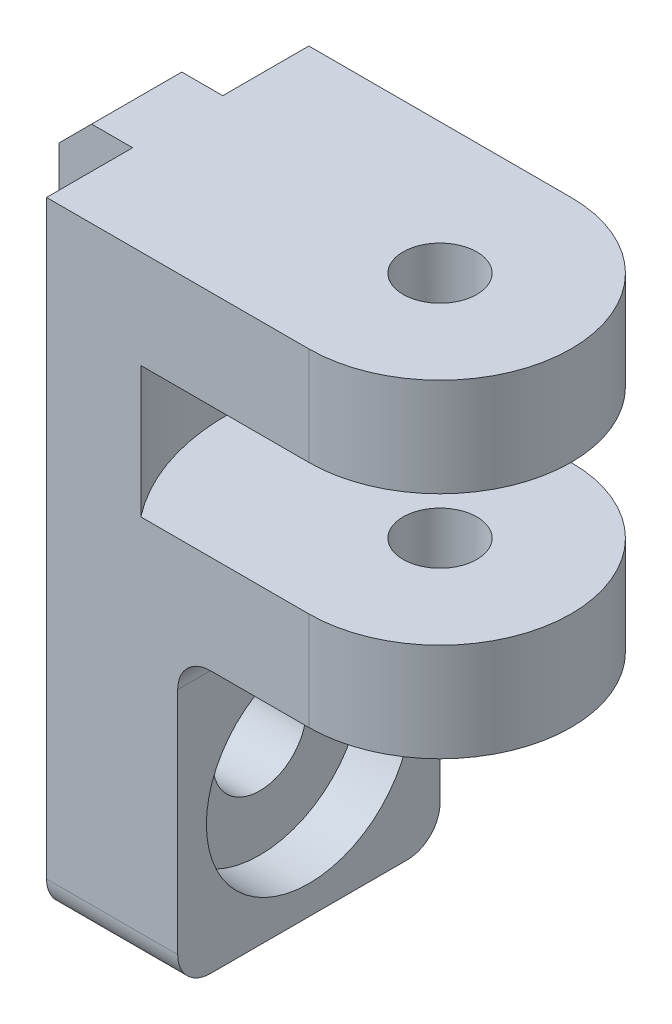
SolidWorks part; units mm, degrees
ref_plane "Front Plane" through (0, 0, 0) normal (0, 0, 1) x (1, 0, 0)
ref_plane "Top Plane" through (0, 0, 0) normal (0, 1, 0) x (1, 0, 0)
ref_plane "Right Plane" through (0, 0, 0) normal (1, 0, 0) x (0, 0, -1)
sketch "Sketch1" plane through (0, 0, 0) normal (1, 0, 0) x (0, 0, -1)
  line L0 (-32.8466, 35.9115) -> (-32.8466, -2.0885)
  line L1 (-48.8466, 35.9115) -> (-32.8466, 35.9115)
  line L5 (-32.8466, -2.0885) -> (-48.8466, -2.0885)
  line L6 (-48.8466, -2.0885) -> (-48.8466, 35.9115)
  dimension "D9" = 16
  dimension "D10" = 38
extrude "Boss-Extrude1" add sketch "Sketch1" along normal blind 8
sketch "Sketch2" plane through (0, 0, 0) normal (-1, 0, 0) x (0, 0, 1)
  line L0 (40.8466, 5.9115) -> (40.8466, 24.9115) construction
  line L1 (48.8466, 35.9115) -> (48.8466, -2.0885) construction
  line L2 (32.8466, 35.9115) -> (48.8466, 35.9115) construction
  line L3 (38.0966, 35.9115) -> (43.5966, 35.9115)
  line L4 (38.0966, 35.9115) -> (38.0966, 13.9115)
  line L5 (38.0966, 13.9115) -> (43.5966, 13.9115)
  line L6 (43.5966, 35.9115) -> (43.5966, 13.9115)
  line L7 (38.0966, 35.9115) -> (43.5966, 13.9115) construction
  line L8 (38.0966, 13.9115) -> (43.5966, 35.9115) construction
  point P5 (40.8466, 24.9115)
  dimension "D1" = 5.5
  dimension "D3" = 8
extrude "Boss-Extrude2" add sketch "Sketch2" along normal blind 4.5
sketch "Sketch6" plane through (0, 35.9115, 0) normal (0, -1, 0) x (1, 0, 0)
  line L0 (8, 48.8466) -> (16, 48.8466)
  line L2 (16, 32.8466) -> (8, 32.8466)
  line L3 (8, 32.8466) -> (8, 48.8466)
  arc A0 (16, 32.8466) -> (16, 48.8466) centre (16, 40.8466) ccw
  circle A1 centre (16, 40.8466) radius 2.25
  dimension "D2" = 4.5
  dimension "D1" = 8
extrude "Boss-Extrude3" add sketch "Sketch6" along normal blind 20 contours A0 L0 L3 L2
fillet "Fillet6" radius 2 1 edges at (8, 15.9115, 40.8466)
chamfer "Chamfer1" distance 2 angle 45 2 edges at (-4.5, 13.9115, 40.8466) (-4.5, 35.9115, 40.8466)
sketch "Sketch7" plane through (8, 0, 0) normal (1, 0, 0) x (0, 0, -1)
  line L0 (-48.8466, -2.0885) -> (-32.8466, -2.0885) construction
  line L1 (-32.8466, -2.0885) -> (-32.8466, 13.9115) construction
  circle A0 centre (-40.8466, 5.9115) radius 2.85
  dimension "D1" = 8
  dimension "D3" = 5.7
  dimension "D2" = 8
extrude "Cut-Extrude1" cut sketch "Sketch7" against normal blind 10
sketch "Sketch8" plane through (8, 0, 0) normal (1, 0, 0) x (0, 0, -1)
  circle A0 centre (-40.8466, 5.9115) radius 6.25
  dimension "D1" = 12.5
extrude "Cut-Extrude2" cut sketch "Sketch8" against normal blind 3
sketch "Sketch9" plane through (0, 35.9115, 0) normal (0, 1, 0) x (1, 0, 0)
  circle A0 centre (16, -40.8466) radius 13
  arc A1 (16, -48.8466) -> (16, -32.8466) centre (16, -40.8466) ccw construction
  dimension "D1" = 5
extrude "Cut-Extrude3" cut sketch "Sketch9" against normal mid plane 8 from offset 10 offset against normal yes
fillet "Fillet7" radius 2 2 edges at (4, -2.0885, 32.8466) (4, -2.0885, 48.8466)
